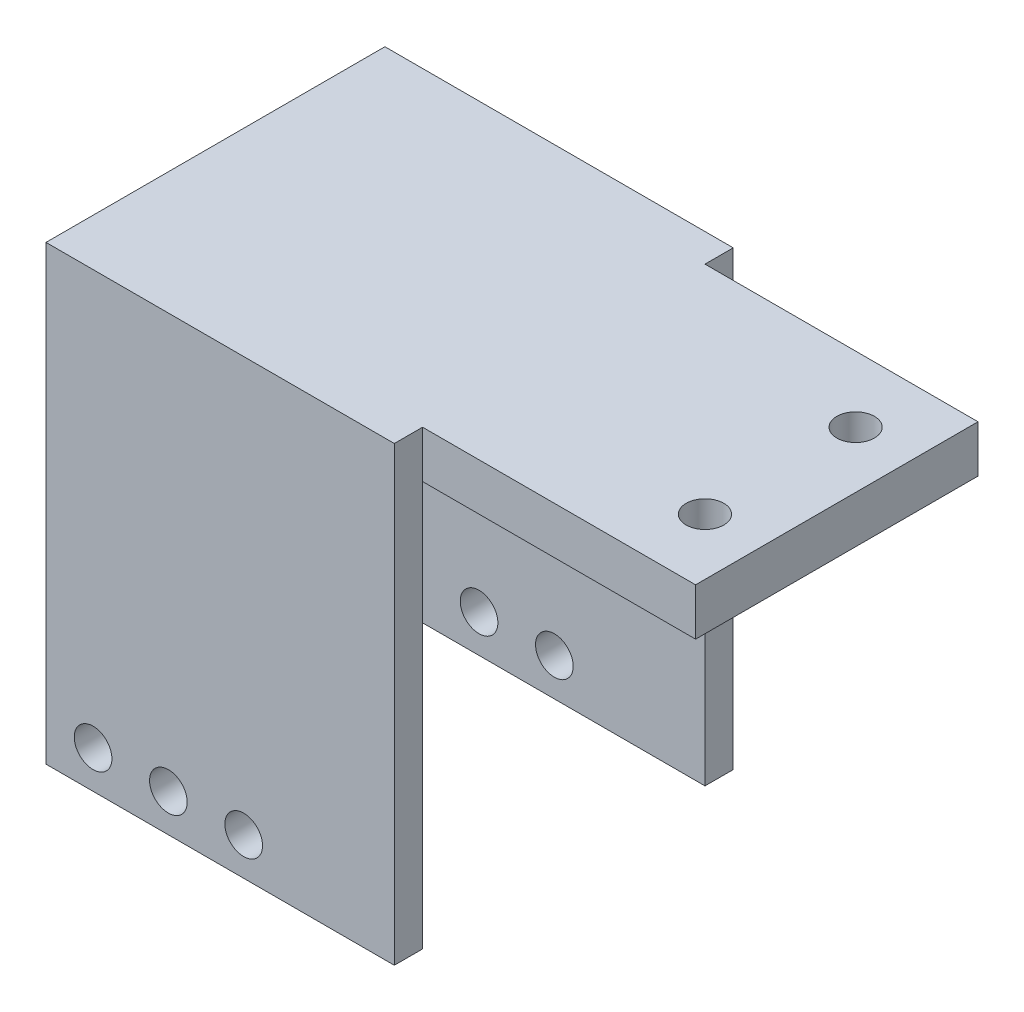
SolidWorks part; units mm, degrees
ref_plane "前基準面" through (0, 0, 0) normal (0, 0, 1) x (1, 0, 0)
ref_plane "上基準面" through (0, 0, 0) normal (0, 1, 0) x (1, 0, 0)
ref_plane "右基準面" through (0, 0, 0) normal (1, 0, 0) x (0, 0, -1)
sketch "草圖1" plane through (0, 0, 0) normal (0, 1, 0) x (1, 0, 0)
  line L1 (0, 0) -> (66, 0)
  line L2 (0, 0) -> (0, 30)
  line L3 (0, 30) -> (66, 30)
  line L4 (66, 0) -> (66, 30)
  circle A0 centre (60, 23) radius 2
  circle A1 centre (60, 7) radius 2
  point P9 (0, 0)
  dimension "D1" = 4
  dimension "D2" = 16
  dimension "D3" = 30
  dimension "D4" = 66
  dimension "D5" = 7
  dimension "D6" = 6
extrude "填料-伸長1" add sketch "草圖1" along normal blind 5
sketch "草圖2" plane through (0, 5, 0) normal (0, 1, 0) x (1, 0, 0)
  line L1 (0, 30) -> (37, 30)
  line L2 (0, 30) -> (0, 33)
  line L3 (0, 33) -> (37, 33)
  line L4 (37, 30) -> (37, 33)
  line L5 (0, 0) -> (37, 0)
  line L6 (0, 0) -> (0, -3)
  line L7 (0, -3) -> (37, -3)
  line L8 (37, 0) -> (37, -3)
  dimension "D1" = 3
  dimension "D2" = 3
  dimension "D3" = 37
  dimension "D4" = 37
extrude "填料-伸長2" add sketch "草圖2" against normal blind 48
sketch "草圖3" plane through (0, 0, 3) normal (0, 0, 1) x (1, 0, 0)
  line L1 (0, -43) -> (37, -43) construction
  line L2 (37, -43) -> (37, 5) construction
  circle A1 centre (21, -39) radius 2
  circle A2 centre (13, -39) radius 2
  circle A3 centre (5, -39) radius 2
  point P10 (0, 0)
  point P11 (0, 0)
  dimension "D3" = 4
  dimension "D5" = 4
  dimension "D1" = 8
  dimension "D2" = 16
  dimension "D6" = 8
  dimension "D7" = 4
extrude "除料-伸長2" cut sketch "草圖3" against normal blind 44
